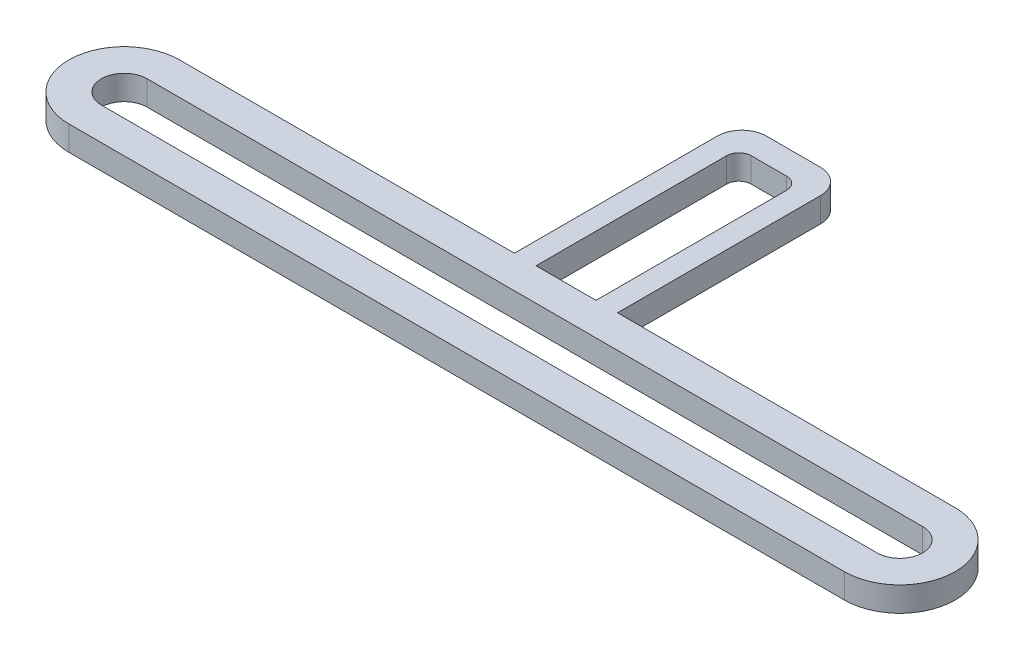
SolidWorks part; units mm, degrees
material "1060 Alloy"
ref_plane "Front Plane" through (0, 0, 0) normal (0, 0, 1) x (1, 0, 0)
ref_plane "Top Plane" through (0, 0, 0) normal (0, 1, 0) x (1, 0, 0)
ref_plane "Right Plane" through (0, 0, 0) normal (1, 0, 0) x (0, 0, -1)
sketch "Sketch1" plane through (0, 0, 0) normal (0, 1, 0) x (1, 0, 0)
  line L0 (-31.8944, 13.0361) -> (48.1635, 13.0361) construction
  line L5 (-31.8944, 18.7547) -> (2.6633, 18.7547)
  line L6 (-31.8944, 7.3176) -> (48.1635, 7.3176)
  line L7 (-31.8944, 13.0361) -> (48.1635, 13.0361) construction
  line L8 (-31.8944, 15.3938) -> (48.1635, 15.3938)
  line L9 (-31.8944, 10.6785) -> (48.1635, 10.6785)
  line L10 (10.5078, 18.7547) -> (11.0867, 18.7547)
  line L20 (13.3119, 18.7547) -> (48.1635, 18.7547)
  line L21 (4.9016, 18.7547) -> (11.0867, 18.7547)
  line L22 (2.6633, 18.7547) -> (2.6633, 39.693)
  line L23 (5.2033, 42.233) -> (10.7719, 42.233)
  line L25 (13.3119, 18.7547) -> (13.3119, 39.693)
  line L26 (4.9016, 18.7547) -> (11.0867, 18.7547)
  line L27 (4.9016, 18.7547) -> (4.9016, 38.423)
  line L28 (6.1716, 39.693) -> (9.8167, 39.693)
  line L29 (11.0867, 18.7547) -> (11.0867, 38.423)
  line L30 (4.9016, 18.7547) -> (5.4578, 18.7547)
  arc A0 (-31.8944, 18.7547) -> (-31.8944, 7.3176) centre (-31.8944, 13.0361) ccw
  arc A1 (48.1635, 7.3176) -> (48.1635, 18.7547) centre (48.1635, 13.0361) ccw
  arc A2 (-31.8944, 15.3938) -> (-31.8944, 10.6785) centre (-31.8944, 13.0361) ccw
  arc A3 (48.1635, 10.6785) -> (48.1635, 15.3938) centre (48.1635, 13.0361) ccw
  arc A6 (10.7719, 42.233) -> (13.3119, 39.693) centre (10.7719, 39.693) cw
  arc A7 (5.2033, 42.233) -> (2.6633, 39.693) centre (5.2033, 39.693) ccw
  arc A8 (9.8167, 39.693) -> (11.0867, 38.423) centre (9.8167, 38.423) cw
  arc A9 (6.1716, 39.693) -> (4.9016, 38.423) centre (6.1716, 38.423) ccw
  point P2 (8.1345, 13.0361)
  point P4 (8.1345, 13.0361)
  point P15 (0, 0)
  point P18 (0, 0)
  point P19 (0, 0)
  point P21 (0, 0)
  point P22 (0, 0)
  point P23 (0, 0)
  point P28 (0, 0)
  point P30 (0, 0)
  point P32 (0, 0)
  point P33 (0, 0)
extrude "Boss-Extrude10" add sketch "Sketch1" along normal blind 2.54 contours L5 L22 A7 L23 A6 L25 L20 A1 L6 A0 | L27 A9 L28 A8 L29 L26 | L9 A3 L8 A2
